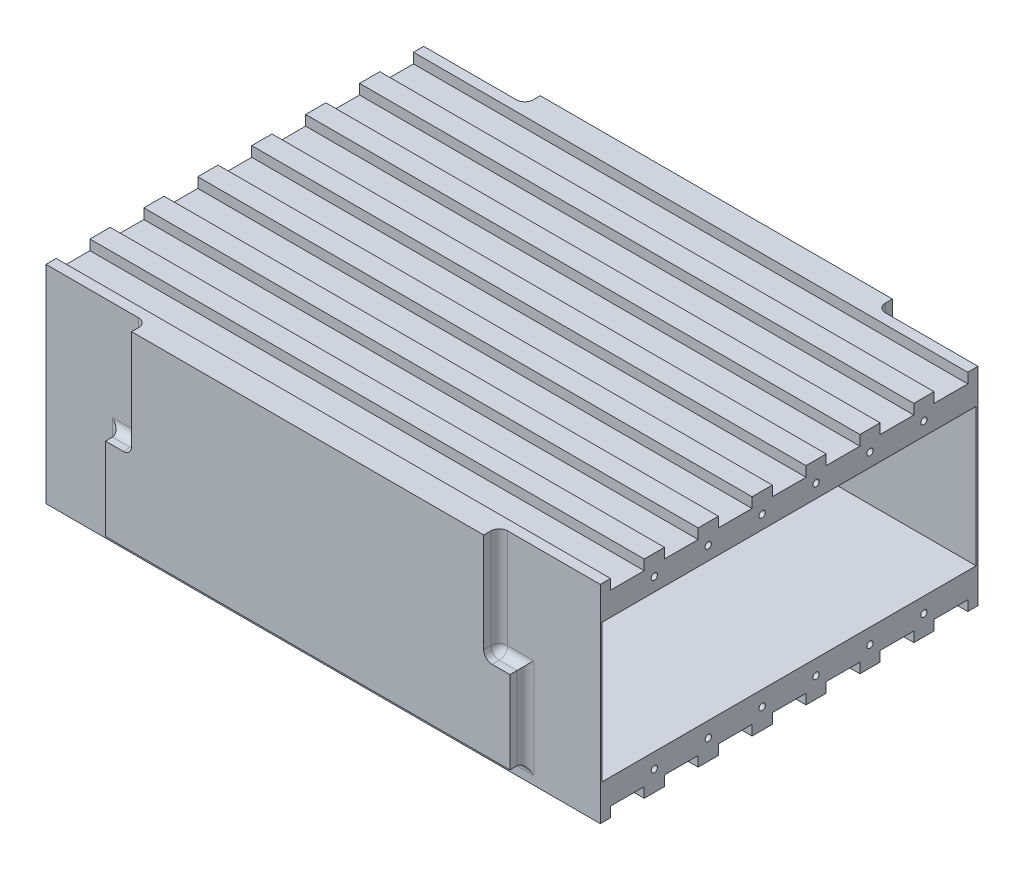
SolidWorks part; units mm, degrees
material "ABS PC"
ref_plane "Front Plane" through (0, 0, 0) normal (0, 0, 1) x (1, 0, 0)
ref_plane "Top Plane" through (0, 0, 0) normal (0, 1, 0) x (1, 0, 0)
ref_plane "Right Plane" through (0, 0, 0) normal (1, 0, 0) x (0, 0, -1)
sketch "Sketch1" plane through (0, 0, 0) normal (0, 1, 0) x (1, 0, 0)
  line L1 (-52.2224, -38.5064) -> (52.2224, -38.5064)
  line L2 (-52.2224, -38.5064) -> (-52.2224, 38.5064)
  line L3 (-52.2224, 38.5064) -> (52.2224, 38.5064)
  line L4 (52.2224, -38.5064) -> (52.2224, 38.5064)
  line L5 (-52.2224, -38.5064) -> (52.2224, 38.5064) construction
  line L6 (-52.2224, 38.5064) -> (52.2224, -38.5064) construction
  point P0 (0, 0)
  dimension "D1" = 77.0128
  dimension "D2" = 104.4448
extrude "Boss-Extrude1" add sketch "Sketch1" along normal blind 32.7025
sketch "Sketch2" plane through (0, 32.7025, 0) normal (0, 1, 0) x (1, 0, 0)
  line L0 (52.2224, -38.5064) -> (52.2224, 38.5064) construction
  line L1 (52.2224, 35.2425) -> (-52.2224, 35.2425)
  line L2 (52.2224, 35.2425) -> (52.2224, -35.2425)
  line L3 (52.2224, -35.2425) -> (-52.2224, -35.2425)
  line L4 (-52.2224, 35.2425) -> (-52.2224, -35.2425)
  line L5 (52.2224, 35.2425) -> (52.2224, 38.5064) construction
  line L6 (52.2224, -35.2425) -> (52.2224, -38.5064) construction
  line L8 (-52.2224, 38.5064) -> (-52.2224, -38.5064) construction
  dimension "D1" = 70.485
extrude "Cut-Extrude1" cut sketch "Sketch2" against normal offset from surface (26.035 mm away) 6.6675 up to face at (0, 0, 0)
sketch "Sketch3" plane through (0, 32.7025, 0) normal (0, 1, 0) x (1, 0, 0)
  line L1 (-52.2224, 38.5064) -> (52.2224, 38.5064)
  line L2 (-52.2224, 38.5064) -> (-52.2224, -38.5064)
  line L3 (-52.2224, -38.5064) -> (52.2224, -38.5064)
  line L4 (52.2224, 38.5064) -> (52.2224, -38.5064)
extrude "Boss-Extrude2" add sketch "Sketch3" along normal blind 6.35
sketch "Sketch4" plane through (0, 39.0525, 0) normal (0, 1, 0) x (1, 0, 0)
  line L1 (52.2224, -38.5064) -> (33.1724, -38.5064)
  line L2 (52.2224, -38.5064) -> (52.2224, -35.5854)
  line L3 (52.2224, -35.5854) -> (33.1724, -35.5854)
  line L4 (33.1724, -38.5064) -> (33.1724, -35.5854)
  dimension "D1" = 2.921
  dimension "D2" = 19.05
extrude "Cut-Extrude2" cut sketch "Sketch4" against normal blind 20.32
sketch "Sketch6" plane through (0, 0, 0) normal (0, -1, 0) x (1, 0, 0)
  line L0 (-52.2224, 38.5064) -> (52.2224, 38.5064) construction
  line L1 (52.2224, 38.5064) -> (38.1, 38.5064)
  line L2 (52.2224, 38.5064) -> (52.2224, 35.5854)
  line L3 (52.2224, 35.5854) -> (38.1, 35.5854)
  line L4 (38.1, 38.5064) -> (38.1, 35.5854)
  point P5 (0, 38.5064)
  dimension "D1" = 2.921
  dimension "D2" = 38.1
extrude "Cut-Extrude3" cut sketch "Sketch6" against normal blind 22.225
mirror "Mirror1" about plane through (0, 0, 0) normal (0, 0, 1) of "Cut-Extrude3", "Cut-Extrude2"
mirror "Mirror2" about plane through (0, 0, 0) normal (1, 0, 0) of "Mirror1", "Cut-Extrude2", "Cut-Extrude3"
sketch "Sketch15" plane through (38.1, 0, 0) normal (1, 0, 0) x (0, 0, -1)
  line L0 (-35.5854, 18.7325) -> (-35.5854, 0) construction
  line L1 (-38.5064, 0) -> (-35.5854, 0)
  line L2 (-38.5064, 0) -> (-38.5064, 3.175)
  line L3 (-38.5064, 3.175) -> (-35.5854, 3.175)
  line L4 (-35.5854, 0) -> (-35.5854, 3.175)
  dimension "D1" = 3.175
extrude "Cut-Extrude5" cut sketch "Sketch15" against normal through all
fillet "Fillet2" radius 1.5875 1 edges at (0, 3.175, 35.5854)
mirror "Mirror6" about plane through (0, 0, 0) normal (0, 0, 1) of "Fillet2", "Cut-Extrude5"
sketch "Sketch5" plane through (0, 0, 38.5064) normal (0, 0, 1) x (1, 0, 0)
  line L0 (33.1724, 18.7325) -> (38.1, 18.7325) construction
  line L1 (36.9824, 18.7325) -> (41.7449, 18.7325)
  line L2 (36.9824, 18.7325) -> (36.9824, 0)
  line L3 (36.9824, 0) -> (41.7449, 0)
  line L4 (41.7449, 18.7325) -> (41.7449, 0)
  line L7 (52.2224, 0) -> (52.2224, 39.0525) construction
  dimension "D1" = 4.7625
  dimension "D2" = 15.24
sketch "Sketch7" [suppressed] plane through (0, 0, 38.7604) normal (0, 0, 1) x (1, 0, 0)
  line L0 (-32.7025, 29.6926) -> (-17.9705, 29.6926) construction
  line L1 (-32.7025, 18.7325) -> (-32.7025, 39.0525) construction
  line L2 (-17.9705, 29.6926) -> (22.6695, 29.6926) construction
  line L3 (-32.7025, 39.0525) -> (32.7025, 39.0525) construction
  dimension "D1" = 40.64
  dimension "D2" = 9.3599
  dimension "D3" = 14.732
hole_wizard "#6 Clearance Hole1" [suppressed] positions "Sketch9" profile "Sketch8" hole size "#6" standard "Ansi Inch"
sketch "Sketch9" [suppressed] plane through (0, 0, 38.7604) normal (0, 0, 1) x (1, 0, 0)
  point P1 (-17.9705, 29.6926)
  point P4 (22.6695, 29.6926)
sketch "Sketch8" plane through (-17.9705, 29.6926, 38.7604) normal (1, 0, 0) x (0, -1, 0)
  line L0 (0, 0) -> (0, 77.5208)
  line L1 (0, 77.5208) -> (1.8986, 77.5208)
  line L2 (1.8986, 77.5208) -> (1.8986, 0)
  line L5 (1.8986, 0) -> (0, 0)
  line L11 (0, -6.35) -> (0, 107.95) construction
  dimension "Thru Hole Dia." = 3.7973
  dimension "Thru Hole Depth" = 77.5208
mirror "Mirror3" [suppressed] about plane through (0, 0, 0) normal (0, 0, 1)
sketch "Sketch10" plane through (-52.2224, 0, 0) normal (-1, 0, 0) x (0, 0, 1)
  line L0 (0, 39.0525) -> (0, 32.7025) construction
  line L1 (-35.5854, 39.0525) -> (35.5854, 39.0525) construction
  line L2 (-35.2425, 32.7025) -> (35.2425, 32.7025) construction
  line L3 (0, 35.2425) -> (-5.08, 35.2425) construction
  line L4 (-5.08, 35.2425) -> (-15.24, 35.2425) construction
  line L5 (-15.24, 35.2425) -> (-25.4, 35.2425) construction
  line L6 (-25.4, 35.2425) -> (-35.56, 35.2425) construction
  line L7 (0, 0) -> (0, 6.6675) construction
  line L8 (-35.5854, 0) -> (35.5854, 0) construction
  line L9 (-35.2425, 6.6675) -> (35.2425, 6.6675) construction
  line L10 (0, 3.81) -> (-5.08, 3.81) construction
  line L11 (-5.08, 3.81) -> (-15.24, 3.81) construction
  line L12 (-15.24, 3.81) -> (-25.4, 3.81) construction
  line L13 (-25.4, 3.81) -> (-35.56, 3.81) construction
  line L14 (-5.08, 35.2425) -> (-5.08, 39.0525) construction
  line L15 (-5.08, 3.81) -> (-5.08, 0) construction
  line L16 (-35.5854, 0) -> (35.5854, 0) construction
  dimension "D1" = 10.16
  dimension "D2" = 5.08
  dimension "D3" = 3.81
hole_wizard "#56 (0.0465) Diameter Hole1" positions "Sketch12" profile "Sketch11" hole size "#56" standard "Ansi Inch"
sketch "Sketch12" plane through (-52.2224, 0, 0) normal (-1, 0, 0) x (0, 0, 1)
  point P1 (-5.08, 35.2425)
  point P4 (-15.24, 35.2425)
  point P7 (-25.4, 35.2425)
  point P16 (-25.4, 3.81)
  point P19 (-15.24, 3.81)
  point P22 (-5.08, 3.81)
sketch "Sketch11" plane through (-52.2224, 35.2425, -5.08) normal (0, 1, 0) x (0, 0, 1)
  line L0 (0, 0) -> (0, 9.8798)
  line L1 (0, 9.8798) -> (0.5905, 9.525)
  line L2 (0.5905, 9.525) -> (0.5905, 0)
  line L5 (0.5905, 0) -> (0, 0)
  line L10 (0, 9.8798) -> (-0.5906, 9.525) construction
  line L11 (0, -6.35) -> (0, 107.95) construction
  dimension "Hole Dia." = 1.1811
  dimension "Hole Depth" = 9.525
  dimension "Drill Angle" = 118
mirror "Mirror4" about plane through (0, 0, 0) normal (0, 0, 1) of "#56 (0.0465) Diameter Hole1"
mirror "Mirror5" about plane through (0, 0, 0) normal (1, 0, 0) of "Mirror4", "#56 (0.0465) Diameter Hole1"
fillet "Fillet1" radius 1.5875 20 edges at (-33.1724, 18.7325, -37.0459) (-33.1724, 28.8925, -35.5854) (-35.6362, 18.7325, -35.5854) (-38.1, 10.16, -35.5854) (-33.1724, 28.8925, 35.5854) (-33.1724, 18.7325, 37.0459) (-35.6362, 18.7325, 35.5854) (-38.1, 10.16, 35.5854) (38.1, 2.71, 36.0504) (-38.1, 2.71, 36.0504) (38.1, 2.71, -36.0504) (-38.1, 2.71, -36.0504) (33.1724, 18.7325, 37.0459) (33.1724, 28.8925, 35.5854) (35.6362, 18.7325, 35.5854) (38.1, 10.16, 35.5854) (33.1724, 28.8925, -35.5854) (33.1724, 18.7325, -37.0459) (35.6362, 18.7325, -35.5854) (38.1, 10.16, -35.5854)
sketch "Sketch13" plane through (-52.2224, 0, 0) normal (-1, 0, 0) x (0, 0, 1)
  line L0 (-35.5854, 39.0525) -> (35.5854, 39.0525) construction
  line L1 (3.175, 39.0525) -> (-3.175, 39.0525)
  line L2 (3.175, 39.0525) -> (3.175, 37.1475)
  line L3 (3.175, 37.1475) -> (-3.175, 37.1475)
  line L4 (-3.175, 39.0525) -> (-3.175, 37.1475)
  line L5 (-35.5854, 0) -> (35.5854, 0) construction
  line L6 (3.175, 0) -> (-3.175, 0)
  line L7 (3.175, 0) -> (3.175, 1.905)
  line L8 (3.175, 1.905) -> (-3.175, 1.905)
  line L9 (-3.175, 0) -> (-3.175, 1.905)
  line L10 (0, 0) -> (0, 1.905) construction
  line L11 (0, 1.905) -> (0, 37.1475) construction
  dimension "D1" = 6.35
  dimension "D2" = 1.905
extrude "Cut-Extrude4" cut sketch "Sketch13" against normal through all
pattern_linear "LPattern1" count 4 spacing 10.16 along (0, 0, 1) count 4 spacing 10.16 along (0, 0, -1) of "Cut-Extrude4"
